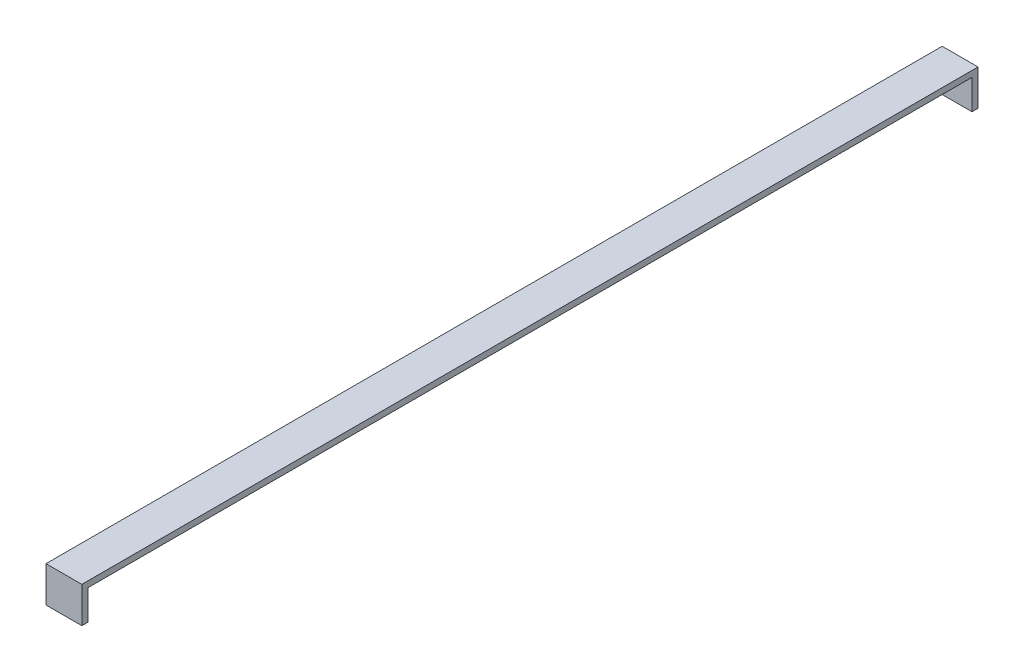
SolidWorks part; units mm, degrees
ref_plane "前视基准面" through (0, 0, 0) normal (0, 0, 1) x (1, 0, 0)
ref_plane "上视基准面" through (0, 0, 0) normal (0, 1, 0) x (1, 0, 0)
ref_plane "右视基准面" through (0, 0, 0) normal (1, 0, 0) x (0, 0, -1)
sketch "草图1" plane through (0, 0, 0) normal (1, 0, 0) x (0, 0, -1)
  line L0 (81.3709, 14.571) -> (82.3709, 14.571)
  line L1 (-67.6291, 20.571) -> (82.3709, 20.571)
  line L2 (-67.6291, 20.571) -> (-67.6291, 14.571)
  line L3 (-67.6291, 14.571) -> (-66.6291, 14.571)
  line L4 (82.3709, 20.571) -> (82.3709, 14.571)
  line L6 (-66.6291, 14.571) -> (-66.6291, 19.571)
  line L7 (-66.6291, 19.571) -> (81.3709, 19.571)
  line L8 (81.3709, 14.571) -> (81.3709, 19.571)
  dimension "D1" = 1
  dimension "D2" = 1
  dimension "D3" = 1
  dimension "D4" = 6
  dimension "D5" = 150
extrude "凸台-拉伸1" add sketch "草图1" along normal blind 6
